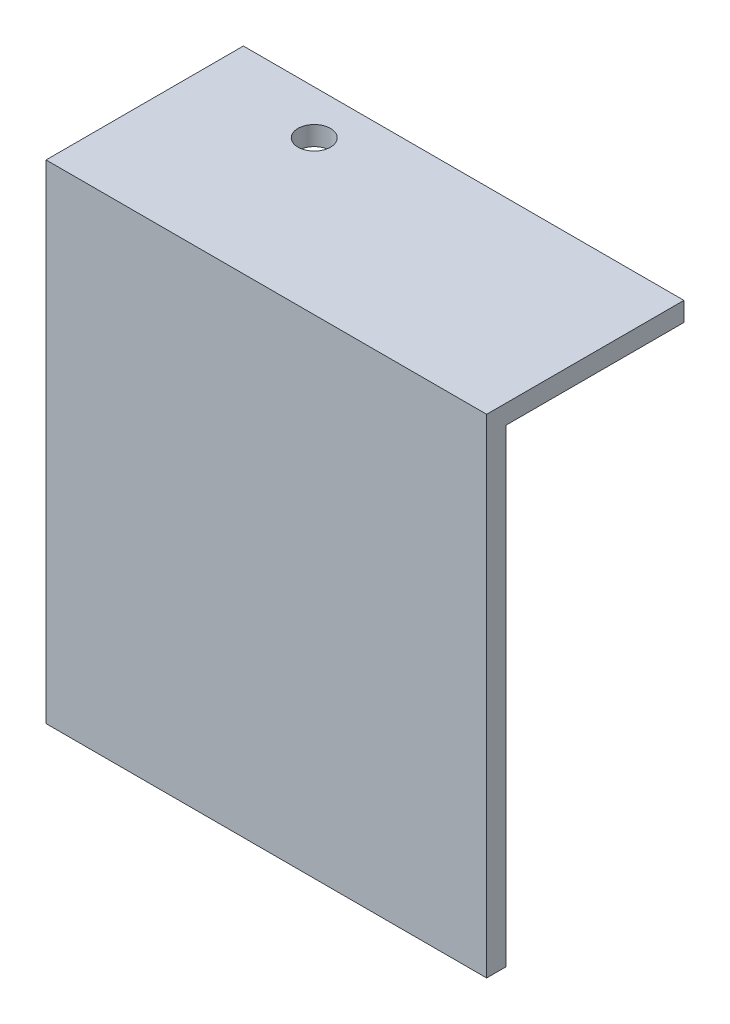
SolidWorks part; units mm, degrees
ref_plane "Front Plane" through (0, 0, 0) normal (0, 0, 1) x (1, 0, 0)
ref_plane "Top Plane" through (0, 0, 0) normal (0, 1, 0) x (1, 0, 0)
ref_plane "Right Plane" through (0, 0, 0) normal (1, 0, 0) x (0, 0, -1)
sketch "Sketch1" plane through (0, 0, 0) normal (0, 0, 1) x (1, 0, 0)
  line L1 (0, 0) -> (115, 0)
  line L2 (0, 0) -> (0, 127.43)
  line L3 (0, 127.43) -> (115, 127.43)
  line L4 (115, 0) -> (115, 127.43)
  dimension "D1" = 115
  dimension "D2" = 127.43
extrude "Boss-Extrude1" add sketch "Sketch1" along normal blind 5 contours L4 L3 L2 L1
sketch "Sketch2" plane through (0, 0, 0) normal (0, 0, -1) x (-1, 0, 0)
  line L0 (0, 0) -> (0, 127.43) construction
  line L1 (-115, 127.43) -> (0, 127.43)
  line L2 (-115, 127.43) -> (-115, 122.43)
  line L3 (-115, 122.43) -> (0, 122.43)
  line L4 (0, 127.43) -> (0, 122.43)
  dimension "D1" = 5
extrude "Boss-Extrude2" add sketch "Sketch2" along normal blind 46.5
sketch "Sketch4" plane through (0, 127.43, 0) normal (0, 1, 0) x (1, 0, 0)
  line L0 (0, -5) -> (0, 46.5) construction
  line L1 (0, -5) -> (115, -5) construction
  circle A0 centre (30, 35) radius 4.25
  dimension "D1" = 8.5
  dimension "D2" = 30
  dimension "D3" = 40
extrude "Cut-Extrude2" cut sketch "Sketch4" against normal through all
